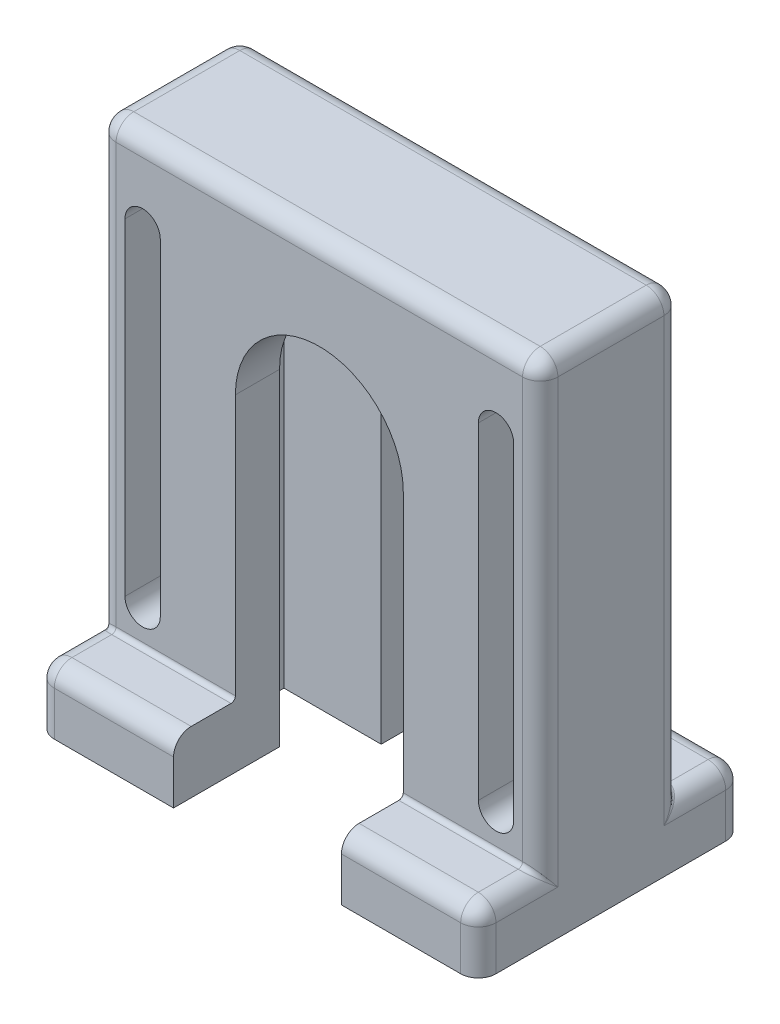
SolidWorks part; units mm, degrees
ref_plane "Front Plane" through (0, 0, 0) normal (0, 0, 1) x (1, 0, 0)
ref_plane "Top Plane" through (0, 0, 0) normal (0, 1, 0) x (1, 0, 0)
ref_plane "Right Plane" through (0, 0, 0) normal (1, 0, 0) x (0, 0, -1)
sketch "Sketch2" plane through (0, 0, 0) normal (0, 1, 0) x (1, 0, 0)
  line L0 (-25, 15) -> (25, 15)
  line L2 (-25, 15) -> (-25, -15)
  line L3 (-25, -15) -> (25, -15)
  line L4 (25, 15) -> (25, -15)
  point P4 (-25, 0)
  dimension "D1" = 50
  dimension "D2" = 30
extrude "Boss-Extrude1" add sketch "Sketch2" along normal blind 7
sketch "Sketch3" plane through (0, 7, 0) normal (0, 1, 0) x (1, 0, 0)
  line L2 (-25, 8) -> (-25, -8)
  line L3 (-25, -8) -> (25, -8)
  line L4 (25, 8) -> (25, -8)
  line L5 (-25, 8) -> (25, 8)
  point P4 (-25, 0)
  point P5 (0, 8)
  dimension "D1" = 16
  dimension "D2" = 50
extrude "Boss-Extrude2" add sketch "Sketch3" along normal blind 50
sketch "Sketch5" plane through (0, 0, 0) normal (0, -1, 0) x (1, 0, 0)
  line L1 (-15, -3) -> (15, -3)
  line L2 (-15, -3) -> (-15, 3)
  line L3 (-15, 3) -> (15, 3)
  line L4 (15, -3) -> (15, 3)
  line L5 (-15, -3) -> (15, 3) construction
  line L6 (-15, 3) -> (15, -3) construction
  line L12 (-25, -8) -> (25, -8)
  line L13 (-25, 8) -> (-25, -8)
  line L14 (25, 8) -> (-25, 8)
  line L15 (25, -8) -> (25, 8)
  line L16 (-25, -8) -> (25, -8)
  line L17 (-25, 8) -> (-25, -8)
  line L18 (25, 8) -> (-25, 8)
  line L19 (25, -8) -> (25, 8)
  point P0 (0, 0)
  dimension "D1" = 6
  dimension "D3" = 30
  dimension "D2" = 0
extrude "Cut-Extrude1" cut sketch "Sketch5" against normal blind 52 contours L1 L4 L3 L2
sketch "Sketch4" plane through (0, 0, 8) normal (0, 0, 1) x (1, 0, 0)
  line L0 (-9.5, 15) -> (-9.5, 37)
  line L1 (-9.5, 15) -> (-9.5, 0)
  line L3 (9.5, 37) -> (9.5, 15)
  line L7 (-25, 0) -> (25, 0) construction
  line L8 (-9.5, 0) -> (9.5, 0)
  line L9 (9.5, 0) -> (9.5, 15)
  arc A1 (9.5, 37) -> (-9.5, 37) centre (0, 37) ccw
  dimension "D1" = 19
extrude "Cut-Extrude3" cut sketch "Sketch4" against normal up to next and the other way up to next
sketch "Sketch6" plane through (0, 0, -8) normal (0, 0, -1) x (-1, 0, 0)
  line L0 (-4, 37) -> (-4, 0)
  line L1 (-25, 0) -> (25, 0) construction
  line L2 (-4, 0) -> (4, 0)
  line L3 (4, 0) -> (4, 37)
  arc A0 (4, 37) -> (-4, 37) centre (0, 37) ccw
  dimension "D1" = 8
extrude "Cut-Extrude4" cut sketch "Sketch6" against normal up to next and the other way up to next
sketch "Sketch8" plane through (0, 0, 8) normal (0, 0, 1) x (1, 0, 0)
  line L6 (-25, 7) -> (-9.5, 7) construction
  line L7 (-22, 48) -> (-22, 11)
  line L8 (-18, 48) -> (-18, 11)
  line L9 (0, -16.5) -> (0, 16.5) construction
  line L10 (18, 48) -> (18, 11)
  line L11 (22, 48) -> (22, 11)
  arc A1 (-18, 48) -> (-22, 48) centre (-20, 48) ccw
  arc A2 (-22, 11) -> (-18, 11) centre (-20, 11) ccw
  arc A3 (22, 11) -> (18, 11) centre (20, 11) cw
  arc A4 (18, 48) -> (22, 48) centre (20, 48) cw
  dimension "D1" = 4
  dimension "D3" = 4
extrude "Cut-Extrude5" cut sketch "Sketch8" against normal up to next
fillet "Fillet1" radius 2 20 edges at (25, 57, 0) (0, 57, 8) (-25, 57, 0) (0, 57, -8) (14.5, 7, -15) (-14.5, 7, -15) (-17.25, 7, 15) (17.25, 7, 15) (25, 3.5, 15) (25, 7, 11.5) (25, 3.5, -15) (25, 7, -11.5) (-25, 3.5, -15) (-25, 7, -11.5) (-25, 3.5, 15) (-25, 7, 11.5) (25, 32, 8) (25, 32, -8) (-25, 32, -8) (-25, 32, 8)
fillet "Fillet2" radius 0.5 8 edges at (24.4142, 6.4142, 7.4142) (-24.4142, 6.4142, 7.4142) (-24.4142, 6.4142, -7.4142) (24.4142, 6.4142, -7.4142) (16.25, 7, 8) (-16.25, 7, 8) (-13.5, 7, -8) (13.5, 7, -8)
